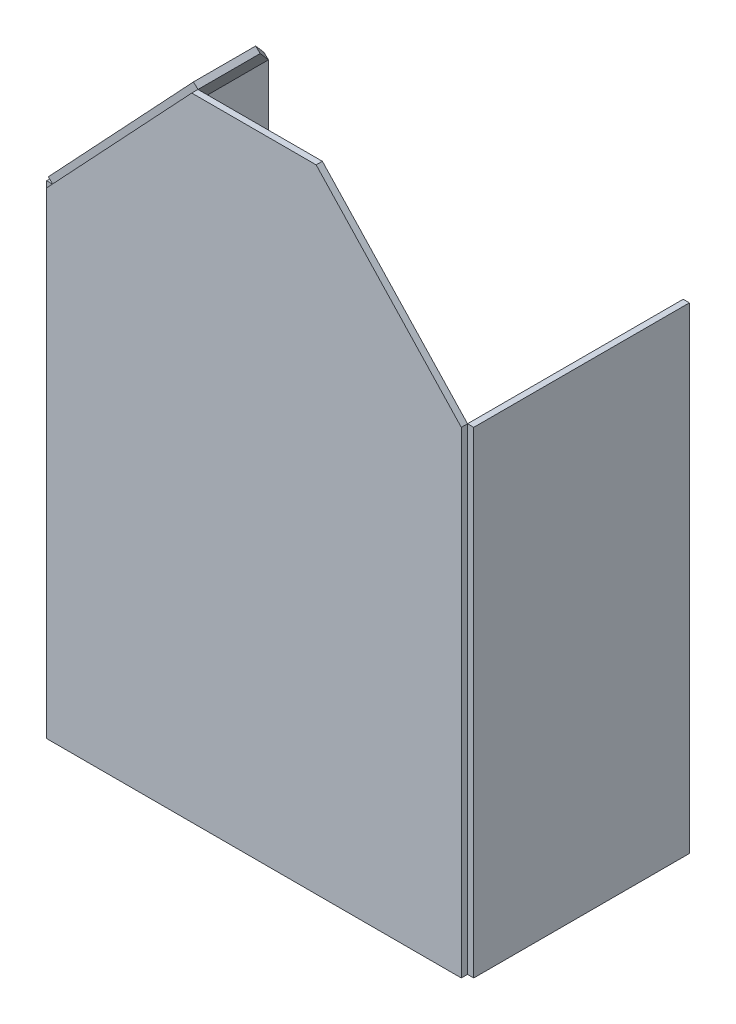
SolidWorks part; units mm, degrees
ref_plane "Plan de face" through (0, 0, 0) normal (0, 0, 1) x (1, 0, 0)
ref_plane "Plan de dessus" through (0, 0, 0) normal (0, 1, 0) x (1, 0, 0)
ref_plane "Plan de droite" through (0, 0, 0) normal (1, 0, 0) x (0, 0, -1)
sketch "Esquisse1" plane through (0, 0, 0) normal (0, 0, 1) x (1, 0, 0)
  line L0 (0, 0) -> (200, 0)
  line L1 (200, 0) -> (200, 230)
  line L2 (200, 230) -> (130, 304.6243)
  line L3 (130, 304.6243) -> (70, 304.6243)
  line L4 (70, 304.6243) -> (0, 230)
  line L5 (0, 230) -> (0, 0)
  point P3 (100, 304.6243)
  point P8 (100, 0)
  point P9 (0, 0)
  dimension "D1" = 200
  dimension "D2" = 230
  dimension "D3" = 230
  dimension "D4" = 70
ref_plane "Plan1" through (-114.7651, 107.6534, 0) normal (-0.7293, 0.6841, 0) x (-0.6841, -0.7293, 0)
ref_plane "Plan2" through (0, 304.6243, 0) normal (0, 1, 0) x (-1, 0, 0)
sketch "Esquisse3" plane through (0, 304.6243, 0) normal (0, 1, 0) x (-1, 0, 0)
  line L0 (-70, 0) -> (-130, 0)
  line L1 (-70, 0) -> (-70, -30)
  line L2 (-130, 0) -> (-130, -30)
  line L3 (-70, -30) -> (-130, -30)
  point P0 (0, 0)
  dimension "D1" = 30
ref_plane "Plan3" through (0, 167.3121, -167.3121) normal (0, -0.7071, 0.7071) x (1, 0, 0)
sketch "Esquisse10" plane through (-114.7651, 107.6534, 0) normal (-0.7293, 0.6841, 0) x (-0.6841, -0.7293, 0)
  line L0 (-167.749, 0) -> (-167.749, -104)
  line L1 (-167.749, -104) -> (-270.066, -30)
  line L2 (-270.066, -30) -> (-270.066, 0)
  line L3 (-270.066, 0) -> (-167.749, 0)
  point P3 (0, 0)
  point P8 (0, 0)
  point P9 (0, 0)
  point P10 (0, 0)
  dimension "D1" = 104
sketch "Esquisse12" plane through (0, 0, 0) normal (1, 0, 0) x (0, 0, -1)
  line L0 (104, 230) -> (0, 230)
  line L1 (104, 230) -> (104, -0.0864)
  line L2 (0, 230) -> (0, -0.0864)
  line L3 (104, -0.0864) -> (0, -0.0864)
ref_plane "Plan4" through (200, 0, 0) normal (1, 0, 0) x (0, 0, -1)
sketch "Esquisse13" plane through (200, 0, 0) normal (1, 0, 0) x (0, 0, -1)
  line L0 (0, 230) -> (0, 0)
  line L1 (0, 230) -> (104, 230)
  line L2 (0, 0) -> (104, 0)
  line L3 (104, 230) -> (104, 0)
  point P0 (0, 0)
  dimension "D1" = 104
extrude "Boss.-Extru.1" add sketch "Esquisse1" along normal blind 3
extrude "Boss.-Extru.2" add sketch "Esquisse10" along normal blind 3 separate body
extrude "Boss.-Extru.3" add sketch "Esquisse13" along normal blind 3 separate body
extrude "Boss.-Extru.4" add sketch "Esquisse12" against normal blind 3 separate body
